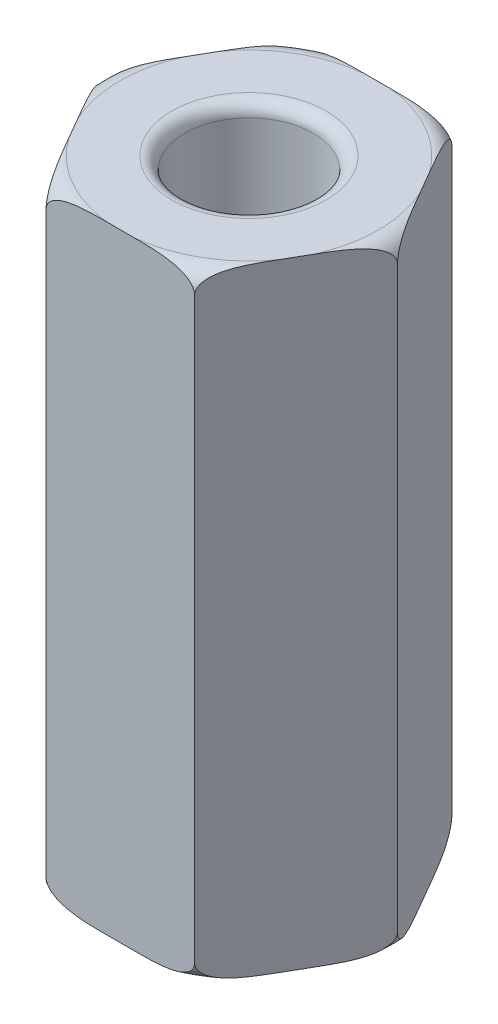
SolidWorks part; units mm, degrees
ref_plane "Front Plane" through (0, 0, 0) normal (0, 0, 1) x (1, 0, 0)
ref_plane "Top Plane" through (0, 0, 0) normal (0, 1, 0) x (1, 0, 0)
ref_plane "Right Plane" through (0, 0, 0) normal (1, 0, 0) x (0, 0, -1)
sketch "Sketch1" plane through (0, 0, 0) normal (0, 1, 0) x (1, 0, 0)
  line L1 (-2.8868, 0) -> (-1.4434, -2.5)
  line L2 (-1.4434, -2.5) -> (1.4434, -2.5)
  line L3 (1.4434, -2.5) -> (2.8868, 0)
  line L4 (2.8868, 0) -> (1.4434, 2.5)
  line L5 (1.4434, 2.5) -> (-1.4434, 2.5)
  line L6 (-1.4434, 2.5) -> (-2.8868, 0)
  circle A0 centre (0, 0) radius 2.5 construction
  point P1 (2.693, -1.0399)
  dimension "D1" = 5
extrude "Boss-Extrude1" add sketch "Sketch1" along normal mid plane 12
sketch "Sketch2" plane through (0, 6, 0) normal (0, 1, 0) x (1, 0, 0)
  circle A0 centre (0, 0) radius 1.25
  dimension "D1" = 2.5
extrude "Cut-Extrude1" cut sketch "Sketch2" against normal up to surface (12 mm away) up to face at (0, -6, 0)
sketch "Sketch3" plane through (0, 0, 0) normal (0, 0, 1) x (1, 0, 0)
  line L1 (2.8868, 6) -> (2.8868, -6) construction
  line L2 (1.4434, 6) -> (2.8868, 6) construction
  line L3 (2.5118, 6) -> (2.8868, 6)
  line L4 (2.8868, 6) -> (2.8868, 5.625)
  line L5 (-4.477, 0) -> (4.6561, 0) construction
  line L6 (2.8868, -6) -> (2.8868, -5.625)
  line L7 (2.5118, -6) -> (2.8868, -6)
  line L8 (0, 5.7216) -> (0, -6.2057) construction
  arc A0 (2.8868, 5.625) -> (2.5118, 6) centre (2.5118, 5.625) ccw
  arc A1 (2.8868, -5.625) -> (2.5118, -6) centre (2.5118, -5.625) cw
  dimension "D1" = 0.75
revolve "Cut-Revolve1" cut sketch "Sketch3" angle 360 about L8
fillet "Fillet1" radius 0.25 2 edges at (0, -6, 1.25) (0, 6, 1.25)
